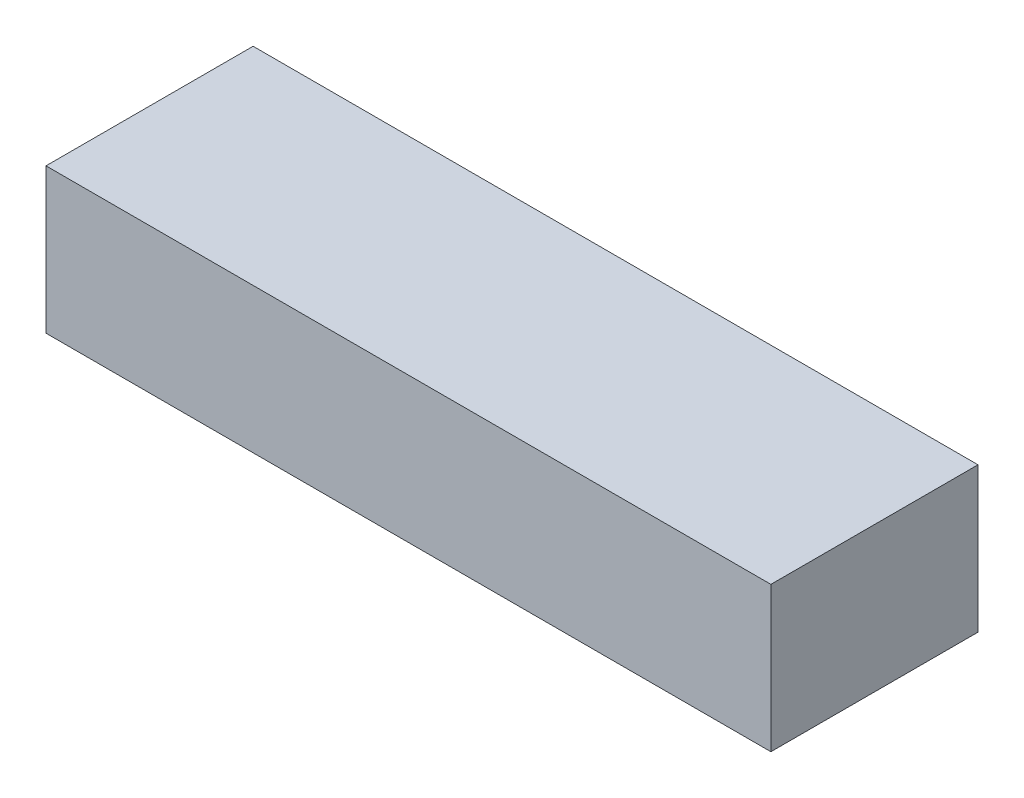
SolidWorks part; units mm, degrees
ref_plane "前视基准面" through (0, 0, 0) normal (0, 0, 1) x (1, 0, 0)
ref_plane "上视基准面" through (0, 0, 0) normal (0, 1, 0) x (1, 0, 0)
ref_plane "右视基准面" through (0, 0, 0) normal (1, 0, 0) x (0, 0, -1)
sketch "草图1" plane through (0, 0, 0) normal (0, 1, 0) x (1, 0, 0)
  line L1 (-8.75, 2.5) -> (8.75, 2.5)
  line L2 (-8.75, 2.5) -> (-8.75, -2.5)
  line L3 (-8.75, -2.5) -> (8.75, -2.5)
  line L4 (8.75, 2.5) -> (8.75, -2.5)
  dimension "D1" = 5
  dimension "D2" = 17.5
  dimension "D3" = 2.5
  dimension "D4" = 8.75
extrude "凸台-拉伸1" add sketch "草图1" along normal blind 3.5
